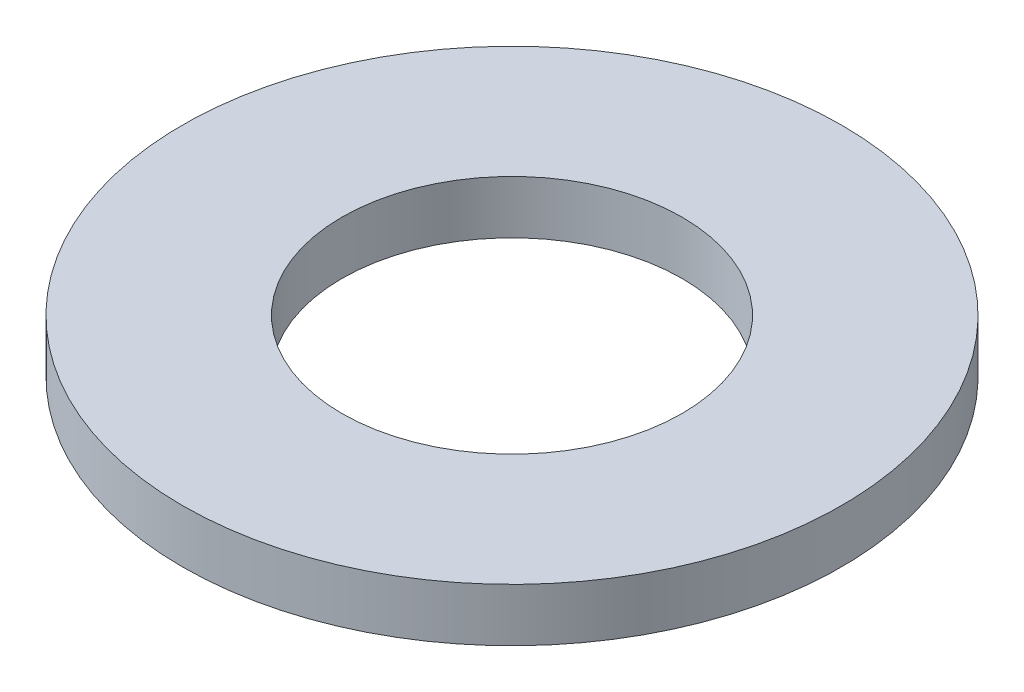
SolidWorks part; units mm, degrees
ref_plane "Front Plane" through (0, 0, 0) normal (0, 0, 1) x (1, 0, 0)
ref_plane "Top Plane" through (0, 0, 0) normal (0, 1, 0) x (1, 0, 0)
ref_plane "Right Plane" through (0, 0, 0) normal (1, 0, 0) x (0, 0, -1)
sketch "Sketch1" plane through (0, 0, 0) normal (0, 1, 0) x (1, 0, 0)
  circle A0 centre (0, 0) radius 3.2
  circle A1 centre (0, 0) radius 6.2
  dimension "D1" = 6.4
  dimension "D2" = 3
extrude "Boss-Extrude1" add sketch "Sketch1" along normal blind 1
